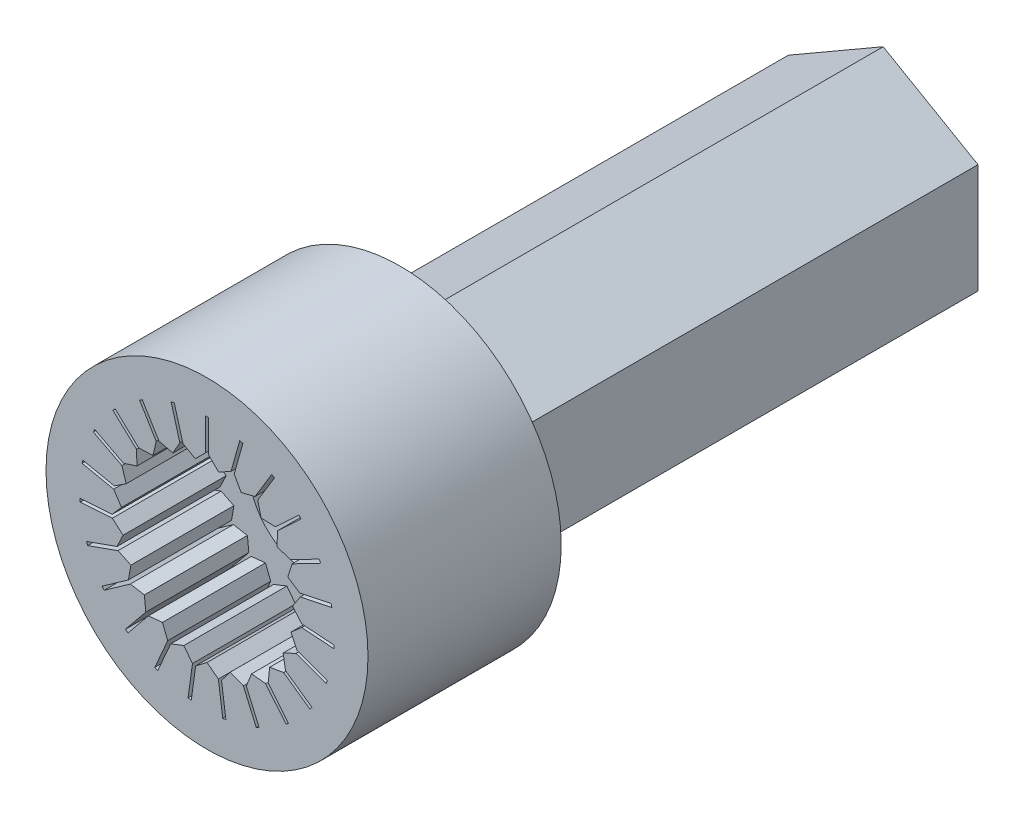
SolidWorks part; units mm, degrees
ref_plane "正面" through (0, 0, 0) normal (0, 0, 1) x (1, 0, 0)
ref_plane "平面" through (0, 0, 0) normal (0, 1, 0) x (1, 0, 0)
ref_plane "右側面" through (0, 0, 0) normal (1, 0, 0) x (0, 0, -1)
sketch "ｽｹｯﾁ1" plane through (0, 0, 0) normal (0, 0, 1) x (1, 0, 0)
  line L1 (0, 3.4) -> (-2.9445, 1.7)
  line L2 (-2.9445, 1.7) -> (-2.9445, -1.7)
  line L3 (-2.9445, -1.7) -> (0, -3.4)
  line L4 (0, -3.4) -> (2.9445, -1.7)
  line L5 (2.9445, -1.7) -> (2.9445, 1.7)
  line L6 (2.9445, 1.7) -> (0, 3.4)
  circle A0 centre (0, 0) radius 2.9445 construction
  dimension "D1" = 6.8
extrude "ﾎﾞｽ - 押し出し1" add sketch "ｽｹｯﾁ1" along normal blind 15
sketch "ｽｹｯﾁ6" plane through (0, 0, 15) normal (0, 0, 1) x (1, 0, 0)
  circle A0 centre (0, 0) radius 5
  dimension "D1" = 10
extrude "ﾎﾞｽ - 押し出し3" add sketch "ｽｹｯﾁ6" along normal blind 6
sketch "ｽｹｯﾁ5" plane through (0, 0, 21) normal (0, 0, 1) x (1, 0, 0)
  line L0 (-0.3625, 2.6375) -> (0, 3) construction
  line L1 (0, 3) -> (0.3625, 2.6375) construction
  line L2 (-0.3625, 2.6375) -> (0, 0) construction
  line L3 (0, 0) -> (0.3625, 2.6375) construction
  line L4 (0, 3) -> (0, 0) construction
  line L5 (-0.05, 2.95) -> (-0.05, 3.95)
  line L6 (-0.05, 3.95) -> (0.05, 3.95)
  line L7 (0.05, 3.95) -> (0.05, 2.95)
  line L8 (-0.05, 2.95) -> (0.05, 2.95) construction
  line L9 (-0.3625, 2.6375) -> (-0.05, 2.95)
  line L10 (-0.05, 2.95) -> (0.05, 2.95) construction
  line L11 (0.3625, 2.6375) -> (0.05, 2.95)
  line L12 (0.3625, 2.6375) -> (0.7478, 2.8541)
  line L13 (0.7478, 2.8541) -> (1.0176, 3.817)
  line L14 (1.1138, 3.79) -> (0.844, 2.8271)
  line L15 (1.0607, 2.4419) -> (0.844, 2.8271)
  line L16 (1.0176, 3.817) -> (1.1138, 3.79)
  line L17 (1.0607, 2.4419) -> (1.4901, 2.5465)
  line L18 (1.4901, 2.5465) -> (2.0096, 3.4009)
  line L19 (2.0951, 3.349) -> (1.5755, 2.4946)
  line L20 (1.6801, 2.0652) -> (1.5755, 2.4946)
  line L21 (2.0096, 3.4009) -> (2.0951, 3.349)
  line L22 (1.6801, 2.0652) -> (2.1218, 2.0501)
  line L23 (2.1218, 2.0501) -> (2.8527, 2.7326)
  line L24 (2.9209, 2.6595) -> (2.1901, 1.977)
  line L25 (2.175, 1.5353) -> (2.1901, 1.977)
  line L26 (2.8527, 2.7326) -> (2.9209, 2.6595)
  line L27 (2.175, 1.5353) -> (2.5963, 1.4016)
  line L28 (2.5963, 1.4016) -> (3.4841, 1.8617)
  line L29 (3.5301, 1.7729) -> (2.6423, 1.3128)
  line L30 (2.5086, 0.8915) -> (2.6423, 1.3128)
  line L31 (3.4841, 1.8617) -> (3.5301, 1.7729)
  line L32 (2.5086, 0.8915) -> (2.8781, 0.6491)
  line L33 (2.8781, 0.6491) -> (3.8572, 0.8526)
  line L34 (3.8776, 0.7547) -> (2.8985, 0.5512)
  line L35 (2.6561, 0.1817) -> (2.8985, 0.5512)
  line L36 (3.8572, 0.8526) -> (3.8776, 0.7547)
  line L37 (2.6561, 0.1817) -> (2.9465, -0.1514)
  line L38 (2.9465, -0.1514) -> (3.9442, -0.2197)
  line L39 (3.9374, -0.3194) -> (2.9397, -0.2512)
  line L40 (2.6066, -0.5417) -> (2.9397, -0.2512)
  line L41 (3.9442, -0.2197) -> (3.9374, -0.3194)
  line L42 (2.6066, -0.5417) -> (2.7964, -0.9408)
  line L43 (2.7964, -0.9408) -> (3.7387, -1.2757)
  line L44 (3.7052, -1.3699) -> (2.7629, -1.035)
  line L45 (2.3638, -1.2248) -> (2.7629, -1.035)
  line L46 (3.7387, -1.2757) -> (3.7052, -1.3699)
  line L47 (2.3638, -1.2248) -> (2.4389, -1.6604)
  line L48 (2.4389, -1.6604) -> (3.2559, -2.237)
  line L49 (3.1982, -2.3187) -> (2.3812, -1.7421)
  line L50 (1.9457, -1.8171) -> (2.3812, -1.7421)
  line L51 (3.2559, -2.237) -> (3.1982, -2.3187)
  line L52 (1.9457, -1.8171) -> (1.9005, -2.2568)
  line L53 (1.9005, -2.2568) -> (2.5316, -3.0325)
  line L54 (2.454, -3.0956) -> (1.8229, -2.3199)
  line L55 (1.3833, -2.2747) -> (1.8229, -2.3199)
  line L56 (2.5316, -3.0325) -> (2.454, -3.0956)
  line L57 (1.3833, -2.2747) -> (1.2211, -2.6859)
  line L58 (1.2211, -2.6859) -> (1.6195, -3.6031)
  line L59 (1.5278, -3.6429) -> (1.1294, -2.7257)
  line L60 (0.7183, -2.5636) -> (1.1294, -2.7257)
  line L61 (1.6195, -3.6031) -> (1.5278, -3.6429)
  line L62 (0.7183, -2.5636) -> (0.4512, -2.9157)
  line L63 (0.4512, -2.9157) -> (0.5874, -3.9064)
  line L64 (0.4883, -3.92) -> (0.3522, -2.9293)
  line L65 (0, -2.6623) -> (0.3522, -2.9293)
  line L66 (0.5874, -3.9064) -> (0.4883, -3.92)
  line L67 (0, -2.6623) -> (-0.3522, -2.9293)
  line L68 (-0.3522, -2.9293) -> (-0.4883, -3.92)
  line L69 (-0.5874, -3.9064) -> (-0.4512, -2.9157)
  line L70 (-0.7183, -2.5636) -> (-0.4512, -2.9157)
  line L71 (-0.4883, -3.92) -> (-0.5874, -3.9064)
  line L72 (-0.7183, -2.5636) -> (-1.1294, -2.7257)
  line L73 (-1.1294, -2.7257) -> (-1.5278, -3.6429)
  line L74 (-1.6195, -3.6031) -> (-1.2211, -2.6859)
  line L75 (-1.3833, -2.2747) -> (-1.2211, -2.6859)
  line L76 (-1.5278, -3.6429) -> (-1.6195, -3.6031)
  line L77 (-1.3833, -2.2747) -> (-1.8229, -2.3199)
  line L78 (-1.8229, -2.3199) -> (-2.454, -3.0956)
  line L79 (-2.5316, -3.0325) -> (-1.9005, -2.2568)
  line L80 (-1.9457, -1.8171) -> (-1.9005, -2.2568)
  line L81 (-2.454, -3.0956) -> (-2.5316, -3.0325)
  line L82 (-1.9457, -1.8171) -> (-2.3812, -1.7421)
  line L83 (-2.3812, -1.7421) -> (-3.1982, -2.3187)
  line L84 (-3.2559, -2.237) -> (-2.4389, -1.6604)
  line L85 (-2.3638, -1.2248) -> (-2.4389, -1.6604)
  line L86 (-3.1982, -2.3187) -> (-3.2559, -2.237)
  line L87 (-2.3638, -1.2248) -> (-2.7629, -1.035)
  line L88 (-2.7629, -1.035) -> (-3.7052, -1.3699)
  line L89 (-3.7387, -1.2757) -> (-2.7964, -0.9408)
  line L90 (-2.6066, -0.5417) -> (-2.7964, -0.9408)
  line L91 (-3.7052, -1.3699) -> (-3.7387, -1.2757)
  line L92 (-2.6066, -0.5417) -> (-2.9397, -0.2512)
  line L93 (-2.9397, -0.2512) -> (-3.9374, -0.3194)
  line L94 (-3.9442, -0.2197) -> (-2.9465, -0.1514)
  line L95 (-2.6561, 0.1817) -> (-2.9465, -0.1514)
  line L96 (-3.9374, -0.3194) -> (-3.9442, -0.2197)
  line L97 (-2.6561, 0.1817) -> (-2.8985, 0.5512)
  line L98 (-2.8985, 0.5512) -> (-3.8776, 0.7547)
  line L99 (-3.8572, 0.8526) -> (-2.8781, 0.6491)
  line L100 (-2.5086, 0.8915) -> (-2.8781, 0.6491)
  line L101 (-3.8776, 0.7547) -> (-3.8572, 0.8526)
  line L102 (-2.5086, 0.8915) -> (-2.6423, 1.3128)
  line L103 (-2.6423, 1.3128) -> (-3.5301, 1.7729)
  line L104 (-3.4841, 1.8617) -> (-2.5963, 1.4016)
  line L105 (-2.175, 1.5353) -> (-2.5963, 1.4016)
  line L106 (-3.5301, 1.7729) -> (-3.4841, 1.8617)
  line L107 (-2.175, 1.5353) -> (-2.1901, 1.977)
  line L108 (-2.1901, 1.977) -> (-2.9209, 2.6595)
  line L109 (-2.8527, 2.7326) -> (-2.1218, 2.0501)
  line L110 (-1.6801, 2.0652) -> (-2.1218, 2.0501)
  line L111 (-2.9209, 2.6595) -> (-2.8527, 2.7326)
  line L112 (-1.6801, 2.0652) -> (-1.5755, 2.4946)
  line L113 (-1.5755, 2.4946) -> (-2.0951, 3.349)
  line L114 (-2.0096, 3.4009) -> (-1.4901, 2.5465)
  line L115 (-1.0607, 2.4419) -> (-1.4901, 2.5465)
  line L116 (-2.0951, 3.349) -> (-2.0096, 3.4009)
  line L117 (-1.0607, 2.4419) -> (-0.844, 2.8271)
  line L118 (-0.844, 2.8271) -> (-1.1138, 3.79)
  line L119 (-1.0176, 3.817) -> (-0.7478, 2.8541)
  line L120 (-0.3625, 2.6375) -> (-0.7478, 2.8541)
  line L121 (-1.1138, 3.79) -> (-1.0176, 3.817)
  circle A0 centre (0, 0) radius 3 construction
  circle A1 centre (0, 0) radius 2.6623 construction
  point P147 (0, 0)
  dimension "D1" = 6
  dimension "D2" = 7.826
  dimension "D3" = 7.826
  dimension "D4" = 0.1
  dimension "D5" = 1
  dimension "D6" = 23
extrude "ｶｯﾄ - 押し出し5" cut sketch "ｽｹｯﾁ5" against normal blind 3.2
chamfer "面取り1" distance 1 angle 45 6 edges at (1.4722, 2.55, 15) (2.9445, 0, 15) (1.4722, -2.55, 15) (-1.4722, -2.55, 15) (-2.9445, 0, 15) (-1.4722, 2.55, 15)
sketch "ｽｹｯﾁ7" plane through (0, 0, 0) normal (0, 0, -1) x (-1, 0, 0)
  circle A0 centre (0, 0) radius 1.9
  dimension "D1" = 3.8
extrude "ｶｯﾄ - 押し出し6" cut sketch "ｽｹｯﾁ7" against normal through all
equation "\"18.4.300mm\"=18.3"
equation "\"D2@ｽｹｯﾁ5\"=360deg/46"
equation "\"D3@ｽｹｯﾁ5\"=\"D2@ｽｹｯﾁ5\""
